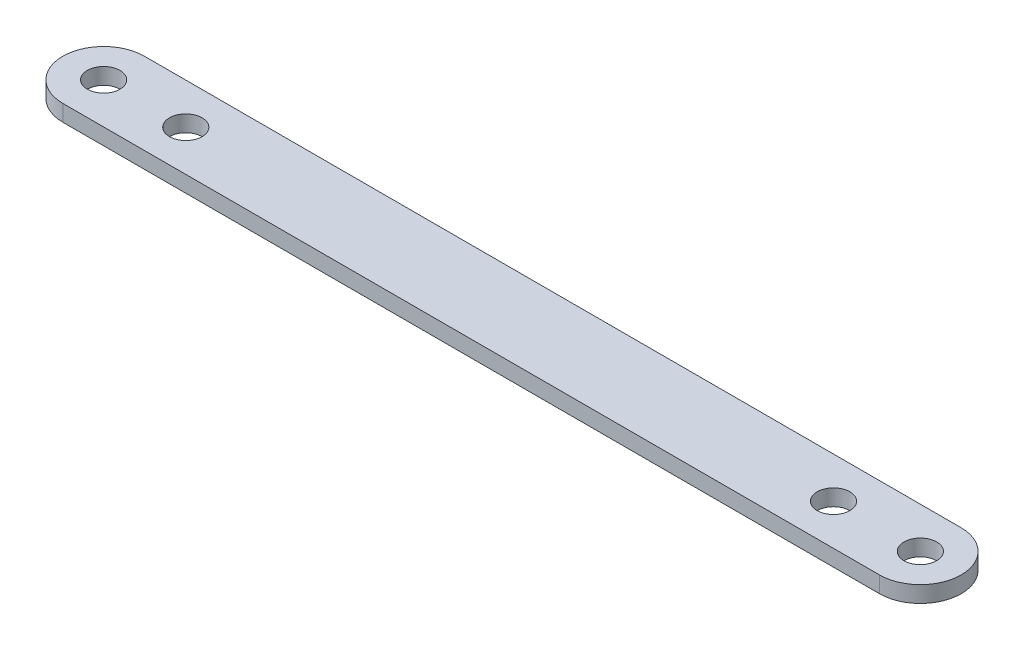
SolidWorks part; units mm, degrees
ref_plane "前视基准面" through (0, 0, 0) normal (0, 0, 1) x (1, 0, 0)
ref_plane "上视基准面" through (0, 0, 0) normal (0, 1, 0) x (1, 0, 0)
ref_plane "右视基准面" through (0, 0, 0) normal (1, 0, 0) x (0, 0, -1)
other "Configuration Table"
sketch "草图1" plane through (0, 0, 0) normal (0, 1, 0) x (1, 0, 0)
  line L0 (0, 0) -> (100, 0) construction
  line L1 (0, 5) -> (100, 5)
  line L2 (0, -5) -> (100, -5)
  arc A0 (0, 5) -> (0, -5) centre (0, 0) ccw
  arc A1 (100, -5) -> (100, 5) centre (100, 0) ccw
  circle A2 centre (0, 0) radius 2.3
  circle A3 centre (100, 0) radius 2.3
  point P3 (50, 0)
extrude "凸台-拉伸1" add sketch "草图1" along normal blind 2 contours A3 | A2 | L1 A1 L2 A0
sketch "草图2" plane through (0, 2, 0) normal (0, 1, 0) x (1, 0, 0)
  circle A0 centre (0, 0) radius 2
  circle A2 centre (0, 0) radius 2.4457
extrude "凸台-拉伸2" add sketch "草图2" against normal blind 2
sketch "草图3" plane through (0, 2, 0) normal (0, 1, 0) x (1, 0, 0)
  circle A0 centre (100, 0) radius 2
  circle A1 centre (100, 0) radius 2.7262
extrude "凸台-拉伸3" add sketch "草图3" against normal blind 2
sketch "草图4" plane through (0, 2, 0) normal (0, 1, 0) x (1, 0, 0)
  circle A0 centre (10.0574, 0) radius 2
  circle A1 centre (89.3664, 0) radius 2
extrude "切除-拉伸1" cut sketch "草图4" against normal blind 2
